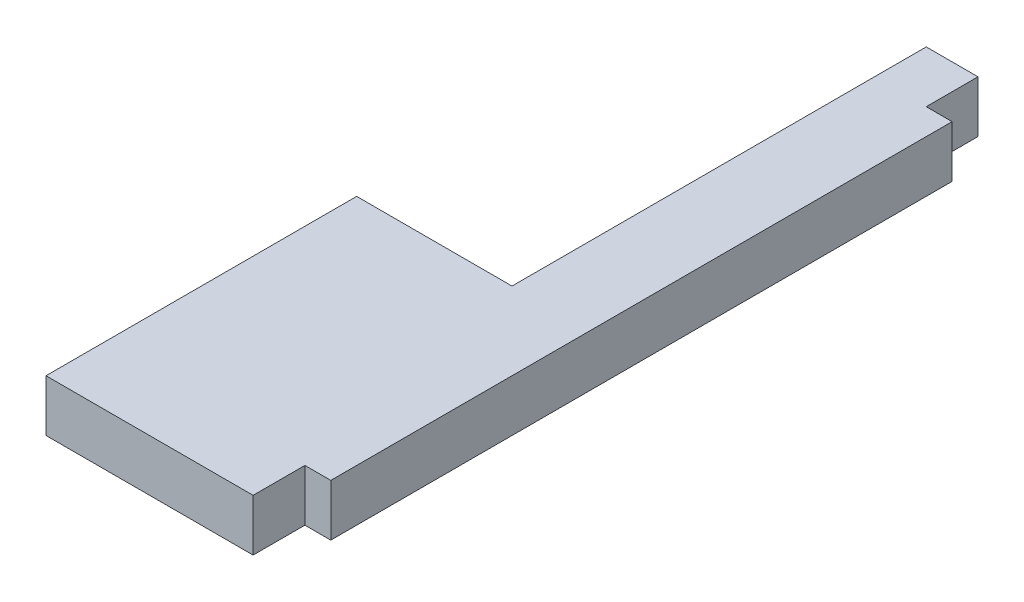
SolidWorks part; units mm, degrees
ref_plane "Front Plane" through (0, 0, 0) normal (0, 0, 1) x (1, 0, 0)
ref_plane "Top Plane" through (0, 0, 0) normal (0, 1, 0) x (1, 0, 0)
ref_plane "Right Plane" through (0, 0, 0) normal (1, 0, 0) x (0, 0, -1)
sketch "Sketch1" plane through (0, 0, 0) normal (0, 1, 0) x (1, 0, 0)
  line L0 (-100.9043, 0) -> (105.8913, 0) construction
  line L1 (0, 56.9353) -> (0, -66.9094) construction
  line L2 (0, 0) -> (-30, 0)
  line L3 (-30, 0) -> (-30, -60)
  line L4 (-30, -60) -> (10, -60)
  line L5 (10, -60) -> (10, -50)
  line L6 (10, -50) -> (15, -50)
  line L7 (15, -50) -> (15, 70)
  line L8 (15, 70) -> (10, 70)
  line L9 (10, 70) -> (10, 80)
  line L10 (10, 80) -> (0, 80)
  line L11 (0, 80) -> (0, 0)
  dimension "D1" = 80
  dimension "D2" = 5
  dimension "D3" = 10
  dimension "D4" = 5
  dimension "D5" = 40
  dimension "D6" = 60
  dimension "D7" = 10
  dimension "D8" = 10
extrude "Boss-Extrude1" add sketch "Sketch1" along normal blind 10
